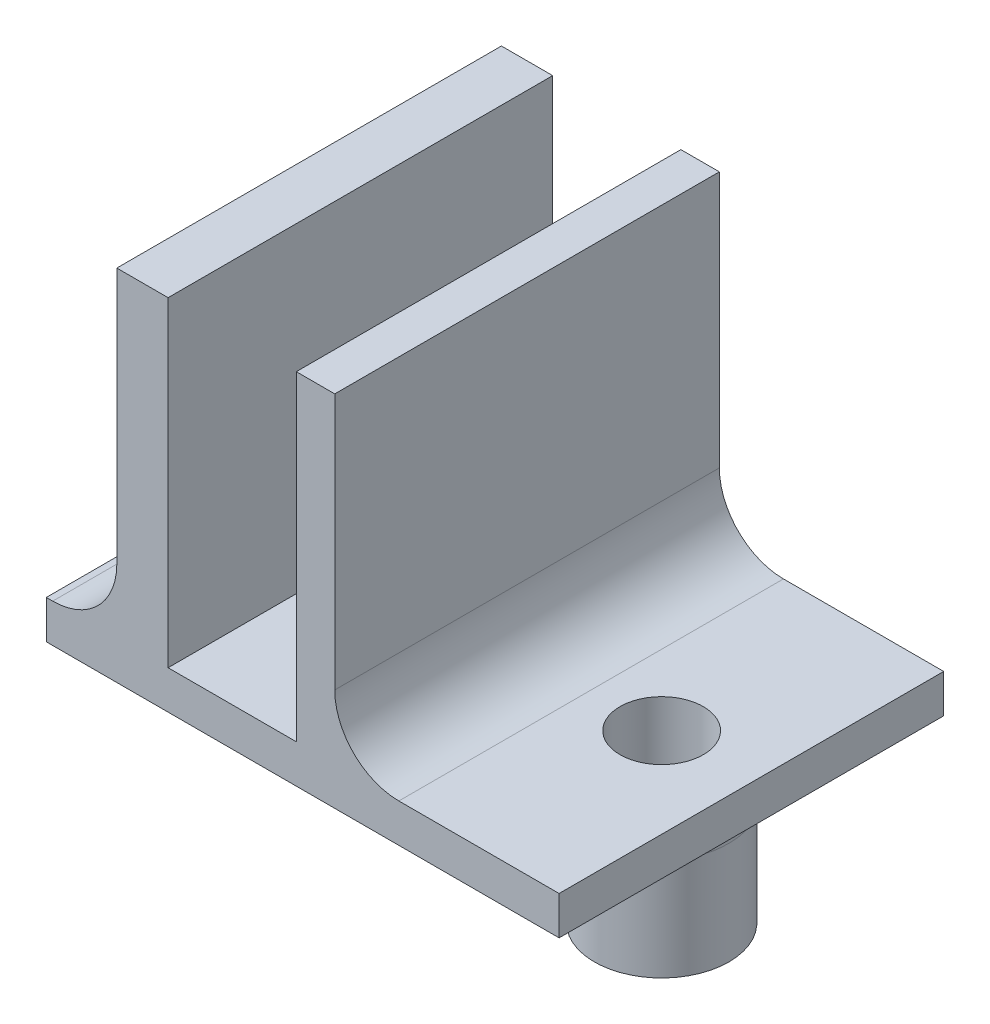
SolidWorks part; units mm, degrees
ref_plane "Plan de face" through (0, 0, 0) normal (0, 0, 1) x (1, 0, 0)
ref_plane "Plan de dessus" through (0, 0, 0) normal (0, 1, 0) x (1, 0, 0)
ref_plane "Plan de droite" through (0, 0, 0) normal (1, 0, 0) x (0, 0, -1)
sketch "Esquisse1" plane through (0, 0, 0) normal (0, 0, 1) x (1, 0, 0)
  line L0 (0, 0) -> (40, 0)
  line L1 (0, 0) -> (0, 3)
  line L2 (0, 3) -> (0.5, 3)
  line L3 (5.5, 8) -> (5.5, 28)
  line L4 (5.5, 28) -> (9.5, 28)
  line L5 (9.5, 28) -> (9.5, 3)
  line L6 (9.5, 3) -> (40, 3)
  line L7 (40, 3) -> (40, 0)
  arc A0 (0.5, 3) -> (5.5, 8) centre (0.5, 8) ccw
  point P11 (5.5, 3)
  dimension "D4" = 5
  dimension "D1" = 25
  dimension "D2" = 40
  dimension "D3" = 4
  dimension "D5" = 3
  dimension "D6" = 9.5
extrude "Boss.-Extru.1" add sketch "Esquisse1" along normal blind 30
sketch "Esquisse2" plane through (0, 3, 0) normal (0, 1, 0) x (1, 0, 0)
  line L0 (33, -15) -> (40, -15) construction
  line L1 (40, -30) -> (40, 0) construction
  circle A0 centre (33, -15) radius 3.25
  dimension "D2" = 6.5
  dimension "D1" = 7
extrude "Enlèv. mat.-Extru.1" cut sketch "Esquisse2" against normal through all
sketch "Esquisse3" plane through (0, 0, 0) normal (0, -1, 0) x (-1, 0, 0)
  circle A0 centre (-33, -15) radius 5.25
  circle A1 centre (-33, -15) radius 3.25 construction
  dimension "D1" = 2
extrude "Extru.-Mince1" add sketch "Esquisse3" along normal blind 10 thin thin type one direction reverse wall 2
sketch "Esquisse5" plane through (0, 0, 30) normal (0, 0, 1) x (1, 0, 0)
  line L0 (40, 3) -> (9.5, 3) construction
  line L1 (19.5, 3) -> (22.5, 3)
  line L2 (19.5, 3) -> (19.5, 28)
  line L3 (19.5, 28) -> (22.5, 28)
  line L4 (22.5, 3) -> (22.5, 28)
  line L5 (9.5, 3) -> (9.5, 28) construction
  dimension "D1" = 25
  dimension "D2" = 3
  dimension "D3" = 10
extrude "Boss.-Extru.3" add sketch "Esquisse5" against normal blind 30
fillet "Congé1" radius 5 1 edges at (22.5, 3, 15)
fillet "Congé2" radius 2 1 edges at (33, 0, 20.25)
sketch "Esquisse6" plane through (0, 0, 30) normal (0, 0, 1) x (1, 0, 0)
  line L0 (29.75, -10) -> (19.75, 0)
  line L1 (0, 0) -> (40, 0) construction
  line L2 (19.75, 0) -> (29.75, 0)
  line L3 (29.75, 0) -> (29.75, -10)
  dimension "D1" = 10
  dimension "D2" = 2
extrude "Extru.-Mince2" add sketch "Esquisse6" against normal blind 10 from offset 10 thin offset against normal yes
